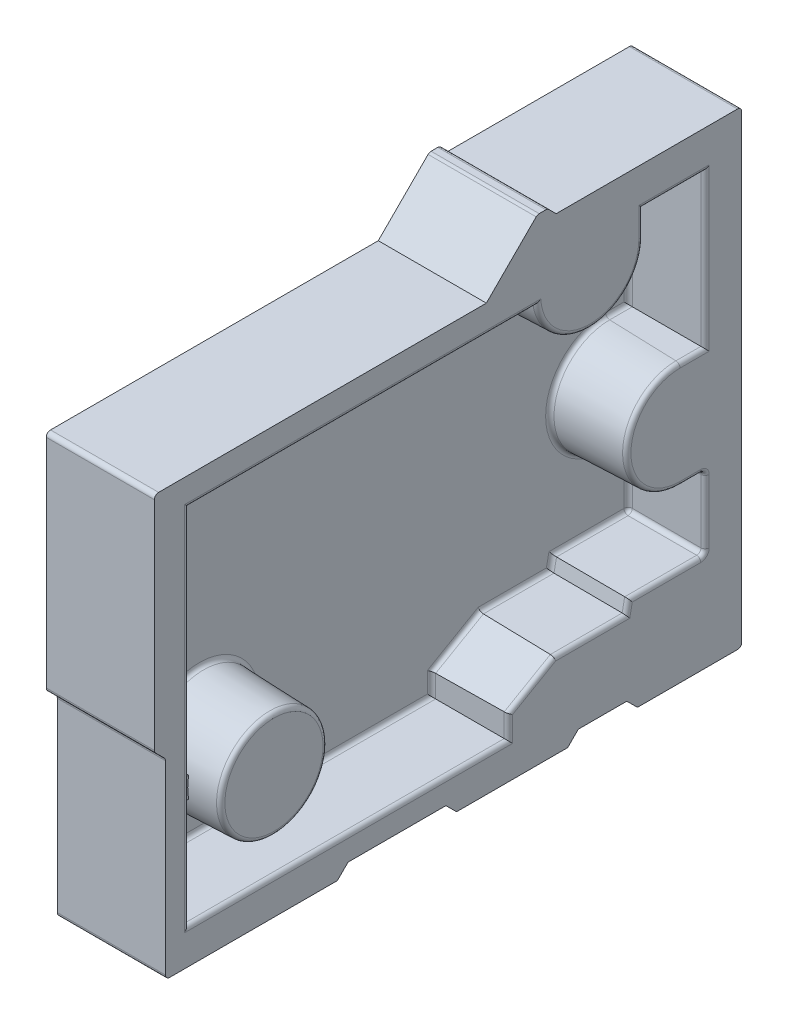
SolidWorks part; units mm, degrees
ref_plane "前视基准面" through (0, 0, 0) normal (0, 0, 1) x (1, 0, 0)
ref_plane "上视基准面" through (0, 0, 0) normal (0, 1, 0) x (1, 0, 0)
ref_plane "右视基准面" through (0, 0, 0) normal (1, 0, 0) x (0, 0, -1)
other "Configuration Table"
sketch "草图1" plane through (0, 0, 0) normal (1, 0, 0) x (0, 0, -1)
  line L0 (-13.8, 10) -> (-13.8, 4.76)
  line L1 (-13.8, 4.76) -> (-13.54, 4.5)
  line L2 (-13.54, 4.5) -> (-13.54, 0)
  line L3 (-13.54, 0) -> (-9.5, 0)
  line L4 (0, 0) -> (0, 11)
  line L5 (0, 11) -> (-4.36, 11)
  line L6 (-4.36, 11) -> (-4.56, 11.2)
  line L7 (-4.56, 11.2) -> (-4.8, 11.2)
  line L8 (-4.8, 11.2) -> (-6, 10)
  line L9 (-6, 10) -> (-13.8, 10)
  line L10 (-9.5, 0) -> (-9.25, 0.25)
  line L11 (-9.25, 0.25) -> (-6.95, 0.25)
  line L12 (-6.95, 0.25) -> (-6.7, 0)
  line L13 (-4.09, 0) -> (-3.84, 0.25)
  line L14 (-3.84, 0.25) -> (-2.7, 0.25)
  line L15 (-2.7, 0.25) -> (-2.45, 0)
  line L16 (-6.7, 0) -> (-4.09, 0)
  line L17 (-2.45, 0) -> (0, 0)
  dimension "D1" = 13.54
  dimension "D2" = 13.8
  dimension "D3" = 135
  dimension "D4" = 11
  dimension "D5" = 11.2
  dimension "D6" = 10
  dimension "D7" = 5.5
  dimension "D8" = 6
  dimension "D9" = 4.36
  dimension "D10" = 0.25
  dimension "D11" = 45
  dimension "D12" = 2.8
  dimension "D13" = 1.64
  dimension "D14" = 2.45
  dimension "D15" = 6.7
extrude "凸台-拉伸1" add sketch "草图1" along normal blind 2.54
sketch "草图13" plane through (2.54, 0, 0) normal (-1, 0, 0) x (0, 0, 1)
  line L0 (0, 0) -> (0, 11) construction
  line L1 (0, 11) -> (4.36, 11) construction
  line L2 (2.45, 0) -> (0, 0) construction
  line L3 (12.99, 9.35) -> (12.99, 0.83)
  line L4 (6.7, 0) -> (4.09, 0) construction
  line L5 (12.99, 0.83) -> (5.48, 0.83)
  line L6 (13.54, 4.5) -> (13.54, 0) construction
  line L7 (5.48, 0.83) -> (5.48, 1.3765)
  line L8 (13.54, 0) -> (9.5, 0) construction
  line L9 (5.48, 1.3765) -> (4.4, 2)
  line L10 (4.4, 2) -> (2.71, 2)
  line L11 (2.71, 2) -> (2.65, 2.3)
  line L12 (2.65, 2.3) -> (0.86, 2.3)
  line L13 (0.86, 2.3) -> (0.86, 4)
  line L14 (0.86, 10.1) -> (2.32, 10.1)
  line L15 (12.99, 9.35) -> (4.8097, 9.35)
  line L16 (2.45, 0) -> (0, 0) construction
  line L17 (6, 10) -> (13.8, 10) construction
  line L18 (13.8, 10) -> (13.8, 4.76) construction
  line L19 (13.54, 0) -> (9.5, 0) construction
  line L20 (0, 0) -> (0, 11) construction
  line L21 (6.7, 0) -> (4.09, 0) construction
  line L22 (0.86, 6.5) -> (0.86, 10.1)
  line L23 (0, 11) -> (4.36, 11) construction
  line L24 (2.32, 9.51) -> (2.32, 10.1)
  line L25 (1.45, 6.5) -> (0.86, 6.5)
  line L26 (1.45, 4) -> (0.86, 4)
  arc A0 (2.32, 9.51) -> (4.8097, 9.35) centre (3.57, 9.51) ccw
  arc A1 (1.45, 4) -> (1.45, 6.5) centre (1.45, 5.25) ccw
  circle A2 centre (1.35, 1.35) radius 0.65 construction
  circle A3 centre (4.35, 1.35) radius 0.5 construction
  circle A4 centre (10.99, 2.9) radius 1.25
  dimension "D1" = 2.5
  dimension "D2" = 2.5
  dimension "D5" = 1.3
  dimension "D6" = 1
  dimension "D7" = 2.5
  dimension "D8" = 1.35
  dimension "D9" = 4.35
  dimension "D10" = 0.65
  dimension "D11" = 0.81
  dimension "D16" = 2.55
  dimension "D17" = 2.9
  dimension "D3" = 3.57
  dimension "D4" = 1.49
  dimension "D12" = 1.45
  dimension "D13" = 5.25
  dimension "D14" = 1.35
  dimension "D15" = 1.35
  dimension "D18" = 0.83
  dimension "D19" = 0.86
  dimension "D20" = 2
  dimension "D21" = 4.4
  dimension "D22" = 2.3
  dimension "D23" = 5.48
  dimension "D24" = 2.71
  dimension "D25" = 2.65
  dimension "D26" = 120
  dimension "D27" = 0.9
extrude "切除-拉伸1" cut sketch "草图13" along normal blind 1.75 draft 2
sketch "草图15" plane through (0.79, 0, 0) normal (1, 0, 0) x (0, 0, -1)
  line L0 (-12.9289, 9.2889) -> (-12.9289, 0.8911) construction
  line L1 (-12.9289, 3.1) -> (-12.2858, 3.1)
  line L2 (-12.9289, 3.1) -> (-12.9289, 2.7)
  line L3 (-12.9289, 2.7) -> (-12.2858, 2.7)
  line L4 (-12.2858, 3.1) -> (-12.2858, 2.7)
  line L5 (-10.99, 2.9) -> (-13.264, 2.9) construction
  circle A0 centre (-10.99, 2.9) radius 1.3111 construction
  point P12 (-12.2858, 2.9)
  dimension "D1" = 0.4
extrude "凸台-拉伸2" add sketch "草图15" along normal blind 1 draft 2.5 draft outward yes
fillet "圆角1" radius 0.1 39 edges at (2.54, 6.5, 1.155) (2.54, 5.25, 2.7) (2.54, 4, 1.155) (2.54, 9.805, 2.32) (1.665, 3.9694, 0.8906) (2.54, 3.15, 0.86) (1.665, 2.3306, 0.8906) (0.79, 3.1, 12.6073) (0.79, 6.1944, 12.9289) (0.79, 9.2889, 8.8956) (0.79, 8.2036, 3.459) (0.79, 9.7744, 2.2589) (0.79, 10.0389, 1.59) (0.79, 8.3, 0.9211) (0.79, 6.5611, 1.1856) (0.79, 5.25, 2.7611) (0.79, 3.9389, 1.1856) (0.79, 3.15, 0.9211) (0.79, 2.3611, 1.8106) (0.79, 2.2111, 2.7301) (0.79, 2.0611, 3.5882) (0.79, 1.7364, 4.9787) (0.79, 1.1514, 5.5411) (0.79, 0.8911, 9.235) (0.79, 1.7956, 12.9289) (0.79, 2.7, 12.6073) (0.79, 2.9, 9.6789) (2.54, 8.2626, 3.4898) (2.54, 10.1, 1.59) (2.54, 8.3, 0.86) (2.54, 2.15, 2.68) (2.54, 2.3, 1.755) (2.54, 2, 3.555) (2.54, 1.6882, 4.94) (2.54, 1.1032, 5.48) (2.54, 0.83, 9.235) (2.54, 5.09, 12.99) (2.54, 2.9, 12.24) (2.54, 9.35, 8.8999)
fillet "圆角2" radius 0.1 8 edges at (1.27, 0, 0) (1.27, 11, 0) (1.27, 11.2, 4.56) (1.27, 11.2, 4.8) (1.27, 10, 13.8) (1.27, 4.76, 13.8) (1.27, 0, 13.54) (1.27, 4.5, 13.54)
